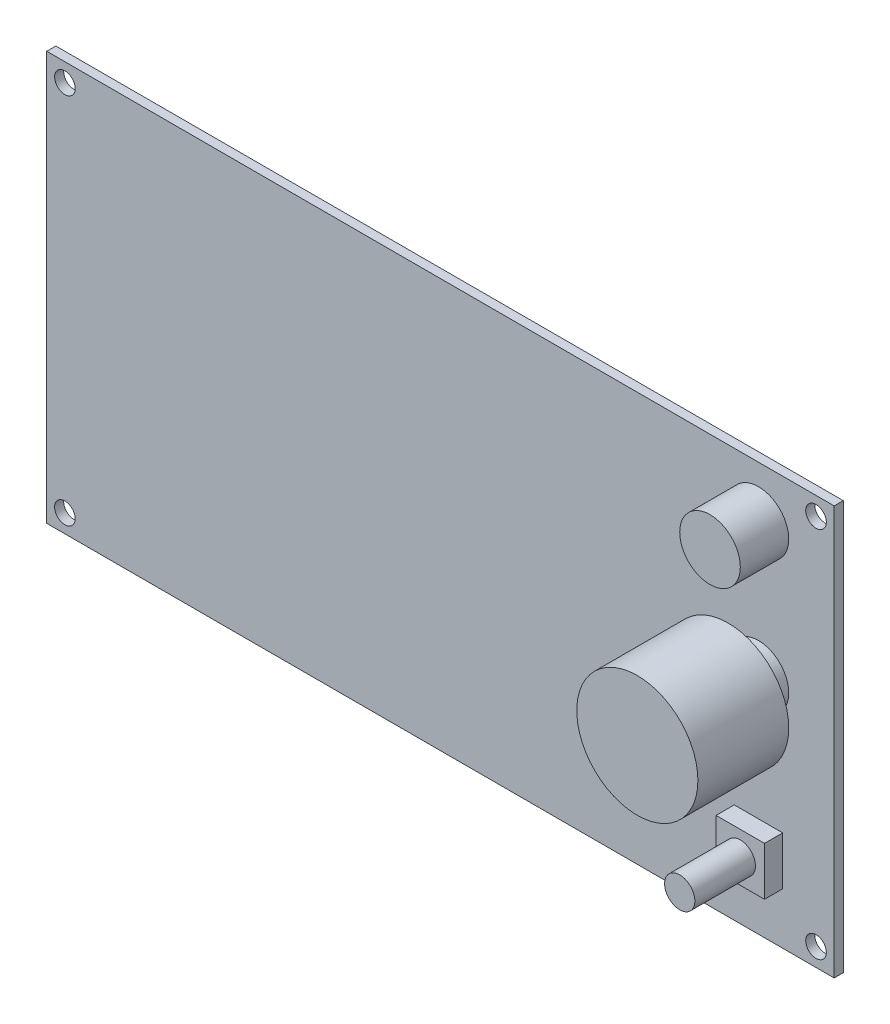
SolidWorks part; units mm, degrees
ref_plane "Front Plane" through (0, 0, 0) normal (0, 0, 1) x (1, 0, 0)
ref_plane "Top Plane" through (0, 0, 0) normal (0, 1, 0) x (1, 0, 0)
ref_plane "Right Plane" through (0, 0, 0) normal (1, 0, 0) x (0, 0, -1)
sketch "Sketch1" plane through (0, 0, 0) normal (0, 0, 1) x (1, 0, 0)
  line L0 (0, 0) -> (124, 0) construction
  line L1 (0, 0) -> (0, 61.5) construction
  line L2 (0, 61.5) -> (124, 61.5) construction
  line L3 (124, 61.5) -> (124, 0) construction
  line L4 (-3, -3) -> (-3, 64.5)
  line L5 (-3, 64.5) -> (127, 64.5)
  line L6 (127, 64.5) -> (127, -3)
  line L7 (-3, -3) -> (127, -3)
  circle A0 centre (0, 0) radius 1.7
  circle A1 centre (0, 61.5) radius 1.7
  circle A2 centre (124, 61.5) radius 1.7
  circle A3 centre (124, 0) radius 1.7
  dimension "D1" = 3.4
  dimension "D5" = 3.4
  dimension "D6" = 3.4
  dimension "D7" = 3.4
  dimension "D2" = 61.5
  dimension "D3" = 124
  dimension "D4" = 124
  dimension "D8" = 3
extrude "Boss-Extrude1" add sketch "Sketch1" along normal blind 1.5
sketch "Sketch2" plane through (0, 0, 1.5) normal (0, 0, 1) x (1, 0, 0)
  line L0 (124, 61.5) -> (114.5, 61.5) construction
  line L1 (114.5, 61.5) -> (114.5, 56) construction
  circle A0 centre (114.5, 56) radius 5
  dimension "D3" = 10
  dimension "D1" = 9.5
  dimension "D2" = 5.5
extrude "Boss-Extrude2" add sketch "Sketch2" along normal blind 8
sketch "Sketch3" plane through (0, 0, 1.5) normal (0, 0, 1) x (1, 0, 0)
  line L0 (114.5, 56) -> (114.5, 34) construction
  circle A0 centre (114.5, 34) radius 5
  dimension "D2" = 10
  dimension "D1" = 22
extrude "Boss-Extrude3" add sketch "Sketch3" along normal blind 5
sketch "Sketch4" plane through (0, 0, 6.5) normal (0, 0, 1) x (1, 0, 0)
  circle A0 centre (114.5, 34) radius 10
  dimension "D1" = 20
extrude "Boss-Extrude4" add sketch "Sketch4" along normal blind 15
sketch "Sketch5" plane through (0, 0, 1.5) normal (0, 0, 1) x (1, 0, 0)
  line L0 (114.5, 34) -> (114.5, 9.5) construction
  line L2 (110.5, 13.5) -> (118.5, 13.5)
  line L3 (110.5, 13.5) -> (110.5, 5.5)
  line L4 (110.5, 5.5) -> (118.5, 5.5)
  line L5 (118.5, 13.5) -> (118.5, 5.5)
  line L6 (110.5, 13.5) -> (118.5, 5.5) construction
  line L7 (110.5, 5.5) -> (118.5, 13.5) construction
  dimension "D1" = 24.5
  dimension "D2" = 8
  dimension "D3" = 8
extrude "Boss-Extrude5" add sketch "Sketch5" along normal blind 3
sketch "Sketch6" plane through (0, 0, 4.5) normal (0, 0, 1) x (1, 0, 0)
  line L0 (118.5, 13.5) -> (110.5, 5.5) construction
  circle A0 centre (114.5, 9.5) radius 2.5
  dimension "D1" = 5
extrude "Boss-Extrude6" add sketch "Sketch6" along normal blind 10
sketch "Sketch7" plane through (0, 0, 0) normal (0, 0, -1) x (-1, 0, 0)
  line L0 (3, 64.5) -> (3, -3) construction
  line L1 (-80, 36.5) -> (-30, 36.5)
  line L2 (-80, 36.5) -> (-80, 29)
  line L3 (-80, 29) -> (-30, 29)
  line L4 (-30, 36.5) -> (-30, 29)
  line L5 (-127, 64.5) -> (3, 64.5) construction
  dimension "D1" = 50
  dimension "D2" = 7.5
  dimension "D3" = 33
  dimension "D4" = 28
extrude "Boss-Extrude7" add sketch "Sketch7" along normal blind 5
sketch "Sketch8" plane through (0, 0, 0) normal (0, 0, -1) x (-1, 0, 0)
  line L0 (3, 64.5) -> (3, -3) construction
  line L1 (-70.5, 0.5) -> (-18.5, 0.5)
  line L2 (-70.5, 0.5) -> (-70.5, -1)
  line L3 (-70.5, -1) -> (-18.5, -1)
  line L4 (-18.5, 0.5) -> (-18.5, -1)
  line L6 (-80, 36.5) -> (-80, 29) construction
  point P8 (-80, 32.75)
  point P9 (-70.5, -0.25)
  dimension "D1" = 1.5
  dimension "D2" = 52
  dimension "D3" = 21.5
  dimension "D4" = 33
extrude "Boss-Extrude8" add sketch "Sketch8" along normal blind 1.5
